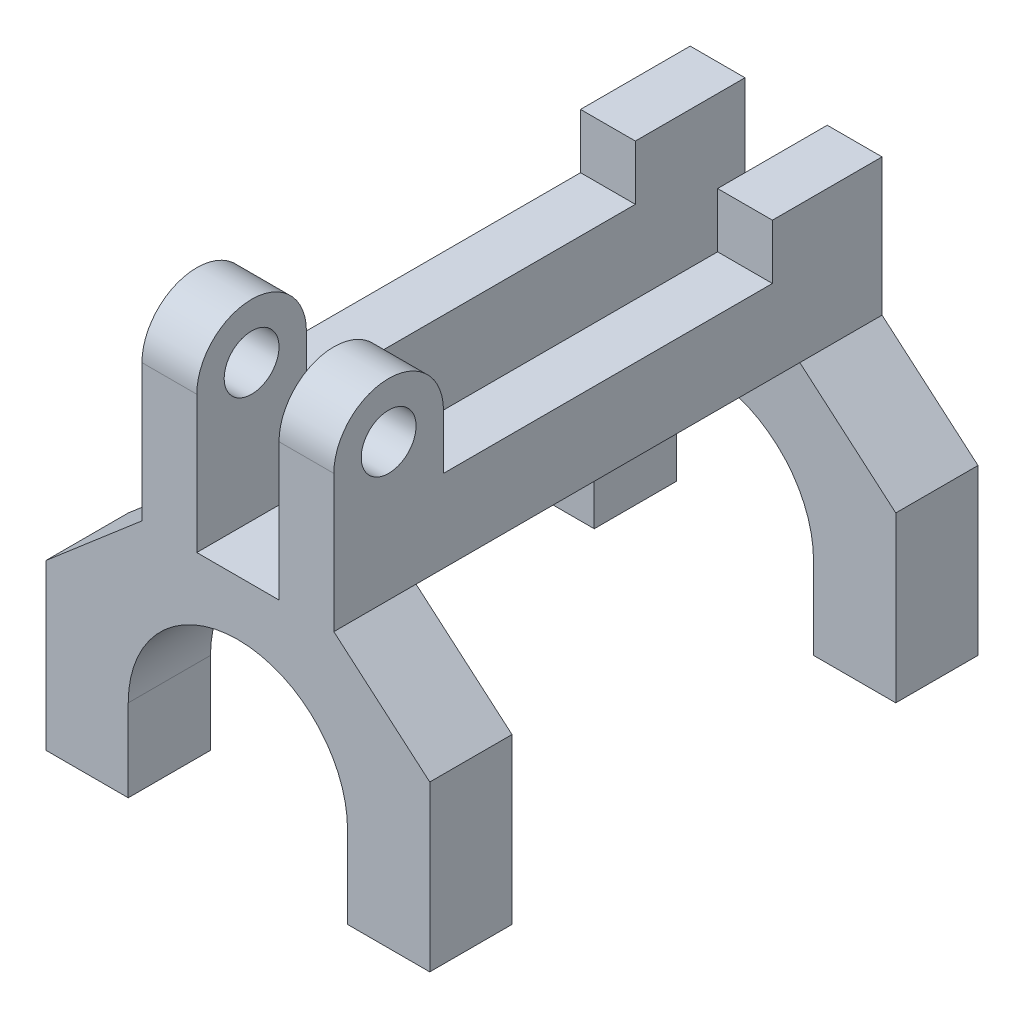
SolidWorks part; units mm, degrees
ref_plane "Front Plane" through (0, 0, 0) normal (0, 0, 1) x (1, 0, 0)
ref_plane "Top Plane" through (0, 0, 0) normal (0, 1, 0) x (1, 0, 0)
ref_plane "Right Plane" through (0, 0, 0) normal (1, 0, 0) x (0, 0, -1)
sketch "Sketch3" plane through (0, 0, 0) normal (0, 0, 1) x (1, 0, 0)
  line L0 (-34.9595, 16.7275) -> (-15.9095, 16.7275)
  line L1 (-34.9595, 16.7275) -> (-34.9595, 54.8275)
  line L2 (-34.9595, 54.8275) -> (-12.7345, 73.8775)
  line L3 (-12.7345, 73.8775) -> (-12.7345, 118.3275)
  line L4 (-12.7345, 118.3275) -> (-0.0345, 118.3275)
  line L5 (-0.0345, 118.3275) -> (-0.0345, 73.8775)
  line L6 (-0.0345, 73.8775) -> (19.0155, 73.8775)
  line L7 (19.0155, 73.8775) -> (19.0155, 118.3275)
  line L8 (19.0155, 118.3275) -> (31.7155, 118.3275)
  line L9 (31.7155, 118.3275) -> (31.7155, 73.8775)
  line L10 (31.7155, 73.8775) -> (53.9405, 54.8275)
  line L11 (53.9405, 54.8275) -> (53.9405, 16.7275)
  line L12 (53.9405, 16.7275) -> (34.8905, 16.7275)
  line L13 (34.8905, 16.7275) -> (34.8905, 35.7775)
  line L14 (-15.9095, 16.7275) -> (-15.9095, 35.7775)
  line L15 (-15.9095, 35.7775) -> (34.8905, 35.7775) construction
  line L16 (-12.7345, 73.8775) -> (31.7155, 73.8775) construction
  line L17 (-34.9595, 54.8275) -> (53.9405, 54.8275) construction
  arc A0 (-15.9095, 35.7775) -> (34.8905, 35.7775) centre (9.4905, 35.7775) cw
  dimension "D6" = 25.4
  dimension "D1" = 19.05
  dimension "D2" = 19.05
  dimension "D3" = 38.1
  dimension "D4" = 44.45
  dimension "D5" = 88.9
  dimension "D7" = 19.05
  dimension "D8" = 44.45
  dimension "D9" = 12.7
  dimension "D10" = 22.225
  dimension "D11" = 19.05
  dimension "D12" = 101.6
extrude "Boss-Extrude1" add sketch "Sketch3" along normal blind 127 contours L9 L10 L11 L12 L13 A0 L14 L0 L1 L2 L3 L4 L5 L6 L7 L8
sketch "Sketch5" plane through (53.9405, 0, 0) normal (1, 0, 0) x (0, 0, -1)
  line L0 (-127, 73.8775) -> (0, 73.8775) construction
  line L1 (-127, 16.7275) -> (-107.95, 16.7275)
  line L2 (-127, 16.7275) -> (-127, 73.8775)
  line L3 (-127, 73.8775) -> (-107.95, 73.8775)
  line L4 (-107.95, 16.7275) -> (-107.95, 73.8775)
  line L6 (0, 16.7275) -> (-19.05, 16.7275)
  line L7 (0, 16.7275) -> (0, 73.8775)
  line L8 (0, 73.8775) -> (-19.05, 73.8775)
  line L9 (-19.05, 16.7275) -> (-19.05, 73.8775)
  line L10 (-107.95, 73.8775) -> (-19.05, 73.8775)
  line L11 (-107.95, 73.8775) -> (-107.95, 16.7275)
  line L12 (-107.95, 16.7275) -> (-19.05, 16.7275)
  line L13 (-19.05, 73.8775) -> (-19.05, 16.7275)
  line M14 (0, 54.8275) -> (-127, 54.8275)
  line M16 (-127, 16.7275) -> (0, 16.7275)
  dimension "D1" = 19.05
  dimension "D2" = 19.05
extrude "Cut-Extrude1" cut sketch "Sketch5" against normal blind 127 contours L9 L4 M16 M14 | L10 L4 L9 M14
sketch "Sketch9" plane through (31.7155, 0, 0) normal (1, 0, 0) x (0, 0, -1)
  line L0 (-127, 118.3275) -> (0, 118.3275) construction
  line L1 (0, 118.3275) -> (-41.3149, 118.3275)
  line L2 (0, 118.3275) -> (0, 105.6275)
  line L3 (0, 105.6275) -> (-25.4, 105.6275)
  line L5 (0, 118.3275) -> (0, 73.8775) construction
  line L7 (-101.6, 118.3275) -> (-41.3149, 118.3275)
  line L8 (-101.6, 118.3275) -> (-101.6, 92.9275)
  line L9 (-101.6, 92.9275) -> (-25.4, 92.9275)
  line L10 (-25.4, 105.6275) -> (-25.4, 92.9275)
  dimension "D1" = 76.2
  dimension "D2" = 25.4
  dimension "D3" = 12.7
  dimension "D4" = 12.7
extrude "Cut-Extrude3" cut sketch "Sketch9" against normal blind 127
sketch "Sketch10" plane through (31.7155, 0, 0) normal (1, 0, 0) x (0, 0, -1)
  line L0 (-127, 105.6275) -> (-127, 118.3275)
  line L5 (-127, 118.3275) -> (-114.3, 118.3275)
  line L6 (-127, 118.3275) -> (-101.6, 118.3275) construction
  line L7 (-114.3, 118.3275) -> (-101.6, 118.3275)
  line L8 (-101.6, 118.3275) -> (-101.6, 105.6275)
  line L9 (-101.6, 118.3275) -> (-101.6, 92.9275) construction
  arc A1 (-127, 105.6275) -> (-114.3, 118.3275) centre (-114.3, 105.6275) cw
  arc A2 (-114.3, 118.3275) -> (-101.6, 105.6275) centre (-114.3, 105.6275) cw
  circle A3 centre (-114.3, 105.6275) radius 6.35
  line M14 (-101.6, 92.9275) -> (-101.6, 118.3275)
  line M15 (-101.6, 118.3275) -> (-127, 118.3275)
  dimension "D1" = 12.7
  dimension "D2" = 12.7
extrude "Cut-Extrude4" cut sketch "Sketch10" against normal blind 127 contours A2 M15 M14 | A3 | A1 L0 L5
sketch "Sketch11" plane through (0, 73.8775, 0) normal (0, 1, 0) x (1, 0, 0)
  line L0 (-0.0345, -25.4) -> (-0.0345, 0) construction
  line L1 (19.0155, -107.95) -> (-0.0345, -107.95)
  line L2 (19.0155, -107.95) -> (19.0155, -19.05)
  line L3 (19.0155, -19.05) -> (-0.0345, -19.05)
  line L4 (-0.0345, -107.95) -> (-0.0345, -19.05)
  line L5 (53.9405, -107.95) -> (31.7155, -107.95) construction
  line L6 (-12.7345, -19.05) -> (-34.9595, -19.05) construction
extrude "Cut-Extrude5" cut sketch "Sketch11" against normal blind 127 contours L1 L4 L3 L2
